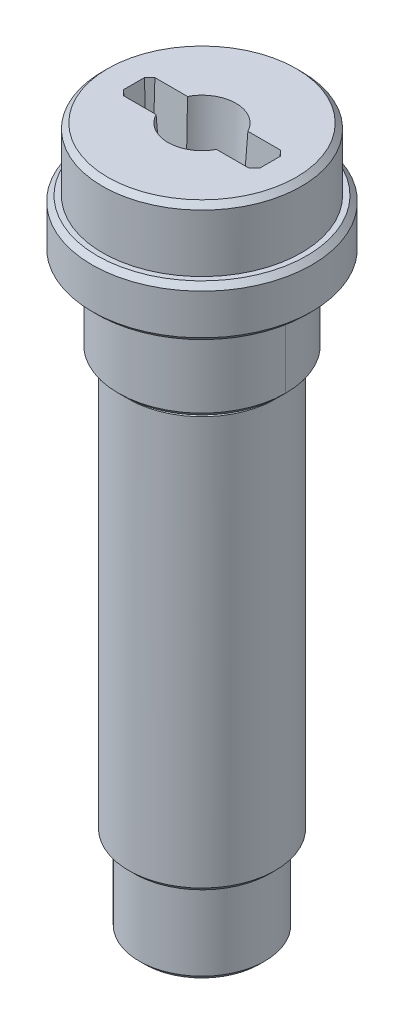
SolidWorks part; units mm, degrees
ref_plane "Front Plane" through (0, 0, 0) normal (0, 0, 1) x (1, 0, 0)
ref_plane "Top Plane" through (0, 0, 0) normal (0, 1, 0) x (1, 0, 0)
ref_plane "Right Plane" through (0, 0, 0) normal (1, 0, 0) x (0, 0, -1)
sketch "Sketch1" plane through (0, 0, 0) normal (1, 0, 0) x (0, 0, -1)
  line L0 (0, 1) -> (0, 66.86)
  line L1 (0, 66.86) -> (9.5, 66.86)
  line L2 (9.5, 66.86) -> (9.5, 60.86)
  line L3 (9.5, 60.86) -> (10.5, 60.86)
  line L4 (10.5, 60.86) -> (10.5, 56)
  line L5 (10.5, 56) -> (5, 56)
  line L6 (5, 56) -> (5, 48)
  line L7 (5, 48) -> (7, 48)
  line L8 (7, 48) -> (7, 8)
  line L9 (7, 8) -> (6, 8)
  line L10 (6, 8) -> (6, 0)
  line L11 (6, 0) -> (1, 0)
  line L12 (1, 0) -> (0, 1)
  dimension "D2" = 8
  dimension "D3" = 1
  dimension "D4" = 40
  dimension "D5" = 2
  dimension "D6" = 8
  dimension "D7" = 5.5
  dimension "D8" = 4.86
  dimension "D9" = 1
  dimension "D10" = 6
  dimension "D11" = 6
  dimension "D12" = 1
  dimension "D13" = 1
revolve "Revolve1" add sketch "Sketch1" angle 360 about L0
chamfer "Chamfer1" distance 0.5 angle 45 6 edges at (0, 56, -10.5) (0, 60.86, -10.5) (0, 48, -7) (0, 66.86, -9.5) (0, 8, -7) (0, 0, -6)
sketch "Sketch2" plane through (0, 66.86, 0) normal (0, 1, 0) x (1, 0, 0)
  line L0 (-6, 1.5) -> (-6.5, 1)
  line L1 (6, -1.5) -> (-6, -1.5)
  line L2 (6.5, -1) -> (6.5, 1)
  line L3 (6, 1.5) -> (-6, 1.5)
  line L4 (-6.5, -1) -> (-6.5, 1)
  line L5 (6.5, -1.5) -> (-6.5, 1.5) construction
  line L6 (6.5, 1.5) -> (-6.5, -1.5) construction
  line L7 (6.5, 1) -> (6, 1.5)
  line L8 (6.5, -1) -> (6, -1.5)
  line L9 (-6, -1.5) -> (-6.5, -1)
  circle A0 centre (0, 0) radius 3.25
  point P0 (0, 0)
  dimension "D3" = 6.5
  dimension "D1" = 3
  dimension "D2" = 13
extrude "Cut-Extrude1" cut sketch "Sketch2" against normal blind 6 draft 3 contours A0 L3 L0 L4 L9 L1 | L3 A0 | L1 A0 L3 | L1 A0 | A0 L1 L8 L2 L7 L3
sketch "Sketch3" plane through (0, 0, 0) normal (0, 0, 1) x (1, 0, 0)
  line L0 (-10, 56) -> (10, 56) construction
  line L1 (-8, 56) -> (-5, 56)
  line L2 (-8, 56) -> (-8, 48)
  line L3 (-8, 48) -> (-5, 48)
  line L4 (-5, 56) -> (-5, 48)
  line L5 (6.5, 48) -> (-6.5, 48) construction
  point P10 (0, 0)
  dimension "D1" = 3
revolve "Revolve2" add sketch "Sketch3" angle 180 about axis through (0, 1, 0) along (0, -1, 0)
chamfer "Chamfer2" distance 0.5 angle 45 8 edges at (0, 56, -5) (-6.5, 56, 0) (0, 56, -8) (6.5, 56, 0) (6.5, 48, 0) (0, 48, -8) (-6.5, 48, 0) (0, 48, -5)
mirror "Mirror1" about plane through (0, 0, 0) normal (0, 0, 1) of bodies 103
